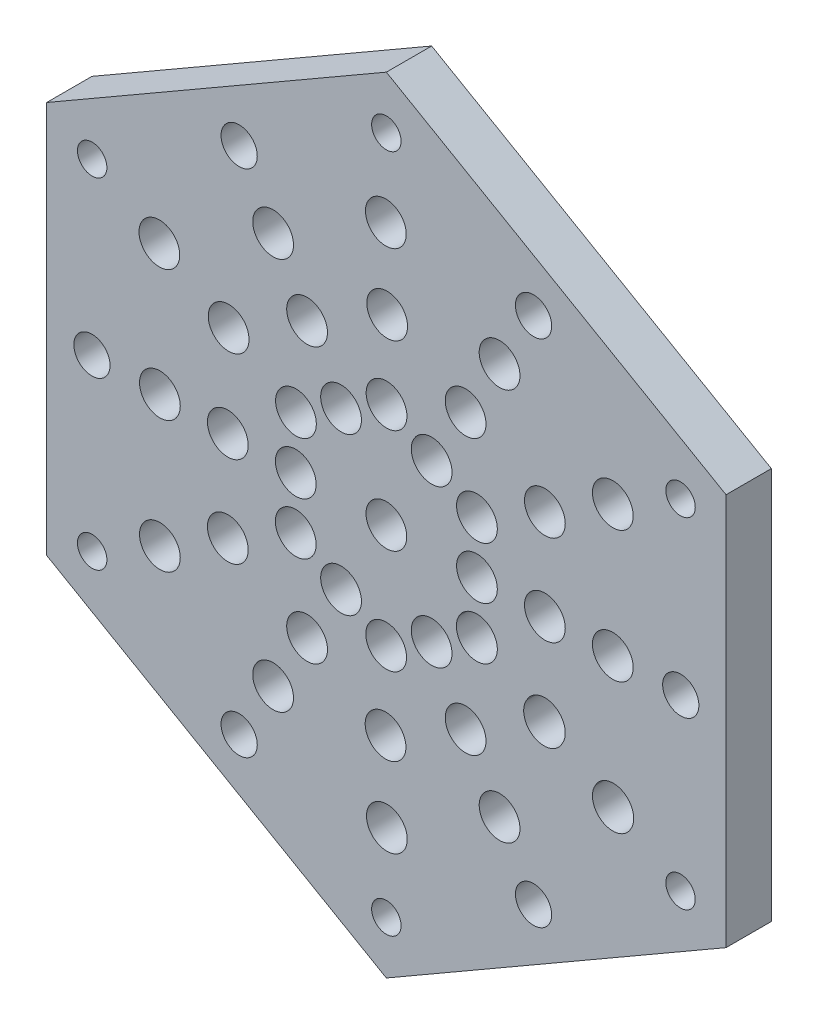
SolidWorks part; units mm, degrees
ref_plane "Front Plane" through (0, 0, 0) normal (0, 0, 1) x (1, 0, 0)
ref_plane "Top Plane" through (0, 0, 0) normal (0, 1, 0) x (1, 0, 0)
ref_plane "Right Plane" through (0, 0, 0) normal (1, 0, 0) x (0, 0, -1)
sketch "Sketch1" plane through (0, 0, 0) normal (0, 0, 1) x (1, 0, 0)
  line L0 (0, 0) -> (0, 75) construction
  line L1 (0, -86.6025) -> (75, -43.3013)
  line L2 (75, -43.3013) -> (75, 43.3013)
  line L3 (75, 43.3013) -> (0, 86.6025)
  line L4 (0, 86.6025) -> (-75, 43.3013)
  line L5 (-75, 43.3013) -> (-75, -43.3013)
  line L6 (-75, -43.3013) -> (0, -86.6025)
  line L7 (0, 0) -> (75, 0) construction
  line L9 (0, 0) -> (20, 0) construction
  line L10 (0, 0) -> (65, 0) construction
  line L11 (0, 0) -> (20, 0) construction
  circle A0 centre (0, 0) radius 75 construction
  circle A1 centre (0, 0) radius 4.5
  circle A2 centre (20, 0) radius 4.5
  circle A3 centre (35, 0) radius 4.5
  circle A4 centre (50, 0) radius 4.5
  circle A5 centre (65, 0) radius 4
  circle A6 centre (0, 75) radius 3.25
  circle A7 centre (64.9519, 37.5) radius 3.25
  circle A8 centre (64.9519, -37.5) radius 3.25
  circle A9 centre (0, -75) radius 3.25
  circle A10 centre (-64.9519, -37.5) radius 3.25
  circle A11 centre (-64.9519, 37.5) radius 3.25
  circle A12 centre (20, 11.5) radius 4.5
  circle A14 centre (20, -11.5) radius 4.5
  circle A15 centre (35, 20) radius 4.5
  circle A16 centre (35, -20) radius 4.5
  circle A17 centre (50, 29) radius 4.5
  circle A18 centre (50, -29) radius 4.5
  circle A19 centre (19.9593, -11.5705) radius 4.5
  circle A20 centre (-0.0407, -23.0705) radius 4.5
  circle A21 centre (-20, -11.5) radius 4.5
  circle A22 centre (-19.9593, 11.5705) radius 4.5
  circle A23 centre (0.0407, 23.0705) radius 4.5
  circle A24 centre (10, -17.3205) radius 4.5
  circle A25 centre (-10, -17.3205) radius 4.5
  circle A26 centre (-20, 0) radius 4.5
  circle A27 centre (-10, 17.3205) radius 4.5
  circle A28 centre (10, 17.3205) radius 4.5
  circle A29 centre (32.5, -56.2917) radius 4
  circle A30 centre (-32.5, -56.2917) radius 4
  circle A31 centre (-65, 0) radius 4
  circle A32 centre (-32.5, 56.2917) radius 4
  circle A33 centre (32.5, 56.2917) radius 4
  circle A34 centre (10, -17.3205) radius 4.5
  circle A35 centre (17.5, -30.3109) radius 4.5
  circle A36 centre (25, -43.3013) radius 4.5
  circle A37 centre (-10, -17.3205) radius 4.5
  circle A38 centre (-17.5, -30.3109) radius 4.5
  circle A39 centre (-25, -43.3013) radius 4.5
  circle A40 centre (-20, 0) radius 4.5
  circle A41 centre (-35, 0) radius 4.5
  circle A42 centre (-50, 0) radius 4.5
  circle A43 centre (-10, 17.3205) radius 4.5
  circle A44 centre (-17.5, 30.3109) radius 4.5
  circle A45 centre (-25, 43.3013) radius 4.5
  circle A46 centre (10, 17.3205) radius 4.5
  circle A47 centre (17.5, 30.3109) radius 4.5
  circle A48 centre (25, 43.3013) radius 4.5
  circle A49 centre (19.9593, -11.5705) radius 4.5
  circle A50 centre (34.8205, -20.3109) radius 4.5
  circle A51 centre (50.1147, -28.8013) radius 4.5
  circle A52 centre (-0.0407, -23.0705) radius 4.5
  circle A53 centre (-0.1795, -40.3109) radius 4.5
  circle A54 centre (0.1147, -57.8013) radius 4.5
  circle A55 centre (-20, -11.5) radius 4.5
  circle A56 centre (-35, -20) radius 4.5
  circle A57 centre (-50, -29) radius 4.5
  circle A58 centre (-19.9593, 11.5705) radius 4.5
  circle A59 centre (-34.8205, 20.3109) radius 4.5
  circle A60 centre (-50.1147, 28.8013) radius 4.5
  circle A61 centre (0.0407, 23.0705) radius 4.5
  circle A62 centre (0.1795, 40.3109) radius 4.5
  circle A63 centre (-0.1147, 57.8013) radius 4.5
  point P146 (0, 0)
  dimension "D2" = 9
  dimension "D3" = 8
  dimension "D4" = 6.5
  dimension "D1" = 150
  dimension "D6" = 75
  dimension "D7" = 20
  dimension "D8" = 15
  dimension "D9" = 15
  dimension "D10" = 15
  dimension "D11" = 10
  dimension "D12" = 11.5
  dimension "D13" = 20
  dimension "D14" = 29
  dimension "D18" = 20
  dimension "D19" = 6
  dimension "D20" = 65
  dimension "D22" = 20
  dimension "D5" = 6
  dimension "D15" = 6
  dimension "D17" = 6
  dimension "D21" = 6
  dimension "D23" = 6
extrude "Boss-Extrude1" add sketch "Sketch1" along normal blind 10 contours L5 L6 L1 L2 L3 L4 A63 A62 A60 A59 A57 A56 A54 A53 A51 A18 A50 A16 A48 A47 A45 A44 A42 A41 A39 A38 A36 A35 A33
